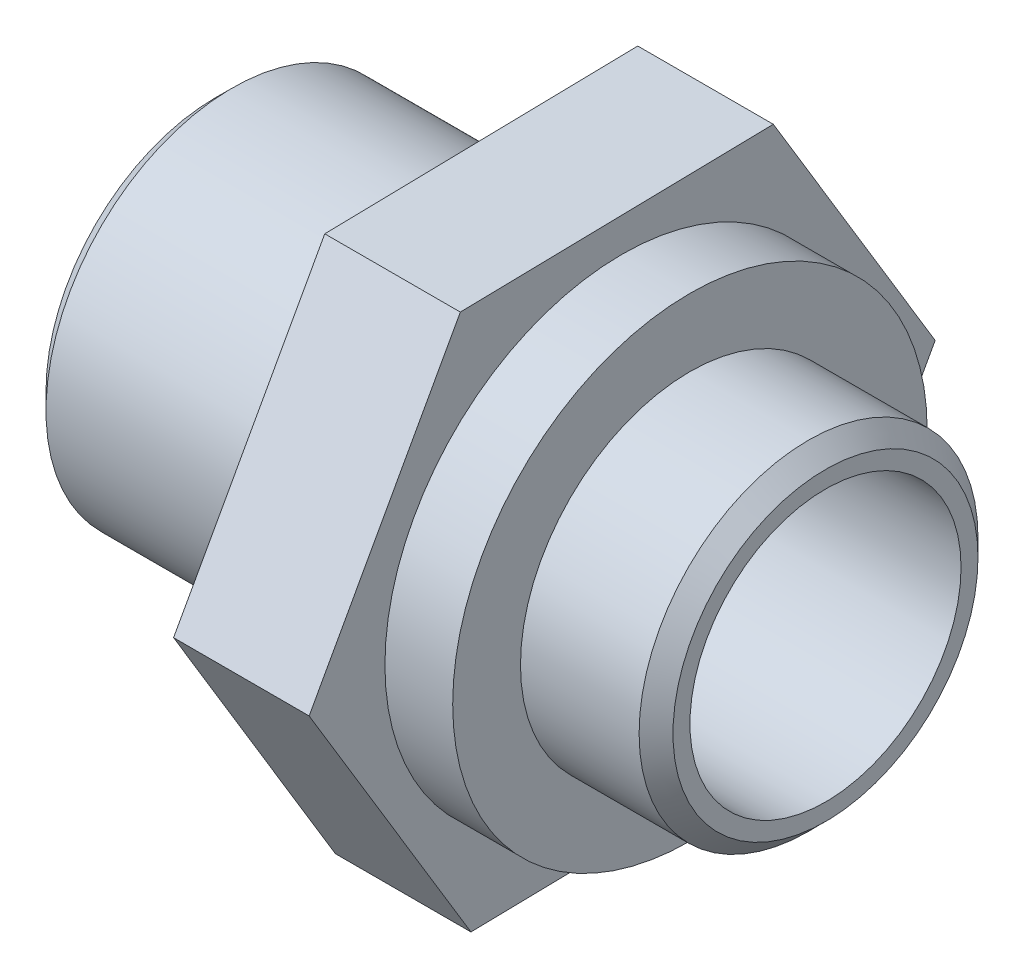
SolidWorks part; units mm, degrees
ref_plane "Front Plane" through (0, 0, 0) normal (0, 0, 1) x (1, 0, 0)
ref_plane "Top Plane" through (0, 0, 0) normal (0, 1, 0) x (1, 0, 0)
ref_plane "Right Plane" through (0, 0, 0) normal (1, 0, 0) x (0, 0, -1)
sketch "Sketch1" plane through (0, 0, 0) normal (1, 0, 0) x (0, 0, -1)
  circle A0 centre (0, 0) radius 2.75
extrude "Boss-Extrude1" add sketch "Sketch1" along normal blind 4
sketch "Sketch2" plane through (4, 0, 0) normal (1, 0, 0) x (0, 0, -1)
  line L2 (2.2307, 4.0444) -> (-2.3873, 3.954)
  line L3 (-2.3873, 3.954) -> (-4.6179, -0.0904)
  line L4 (-4.6179, -0.0904) -> (-2.2307, -4.0444)
  line L5 (-2.2307, -4.0444) -> (2.3873, -3.954)
  line L6 (2.3873, -3.954) -> (4.6179, 0.0904)
  line L7 (4.6179, 0.0904) -> (2.2307, 4.0444)
  circle A0 centre (0, 0) radius 4 construction
  dimension "D1" = 8
extrude "Boss-Extrude2" add sketch "Sketch2" along normal blind 2
sketch "Sketch3" plane through (6, 0, 0) normal (1, 0, 0) x (0, 0, -1)
  circle A0 centre (0, 0) radius 3.5
extrude "Boss-Extrude3" add sketch "Sketch3" along normal blind 1
sketch "Sketch4" plane through (7, 0, 0) normal (1, 0, 0) x (0, 0, -1)
  circle A0 centre (0, 0) radius 2.5
extrude "Boss-Extrude4" add sketch "Sketch4" along normal blind 2
sketch "Sketch5" plane through (9, 0, 0) normal (1, 0, 0) x (0, 0, -1)
  circle A0 centre (0, 0) radius 2
extrude "Cut-Extrude1" cut sketch "Sketch5" against normal through all
chamfer "Chamfer1" distance 0.25 angle 45 2 edges at (0, 0, -2.75) (9, 0, -2.5)
